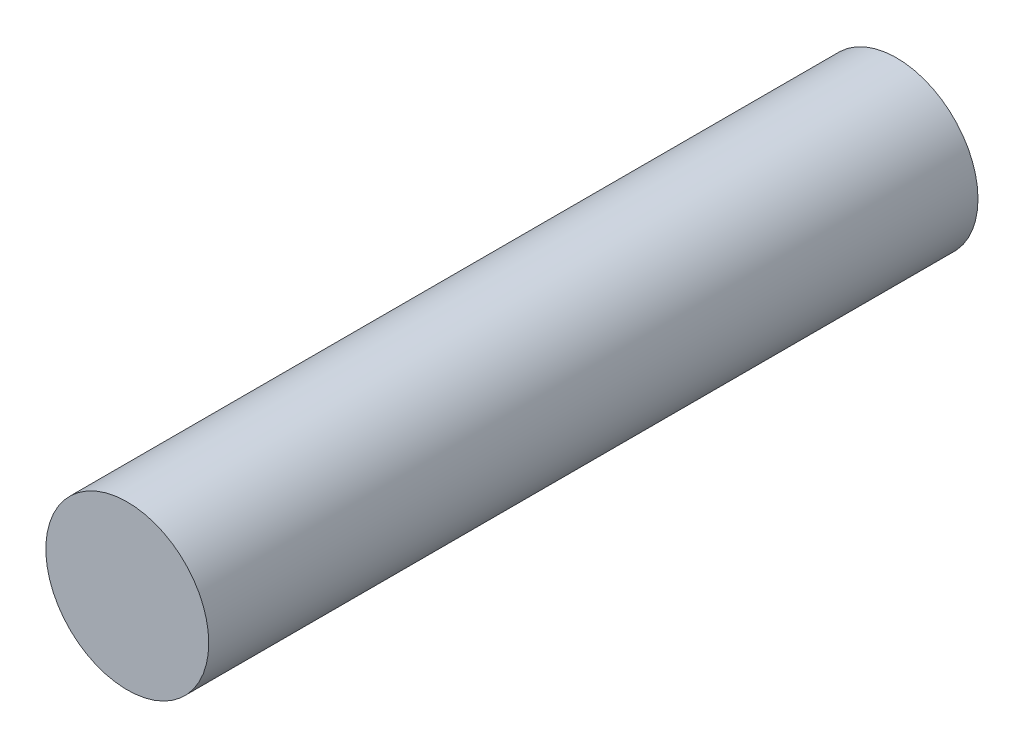
SolidWorks part; units mm, degrees
ref_plane "Front Plane" through (0, 0, 0) normal (0, 0, 1) x (1, 0, 0)
ref_plane "Top Plane" through (0, 0, 0) normal (0, 1, 0) x (1, 0, 0)
ref_plane "Right Plane" through (0, 0, 0) normal (1, 0, 0) x (0, 0, -1)
sketch "Sketch1" plane through (0, 0, 0) normal (0, 0, 1) x (1, 0, 0)
  circle A0 centre (0, 0) radius 1.8
  dimension "D1" = 3.6
extrude "Boss-Extrude1" add sketch "Sketch1" along normal blind 17
